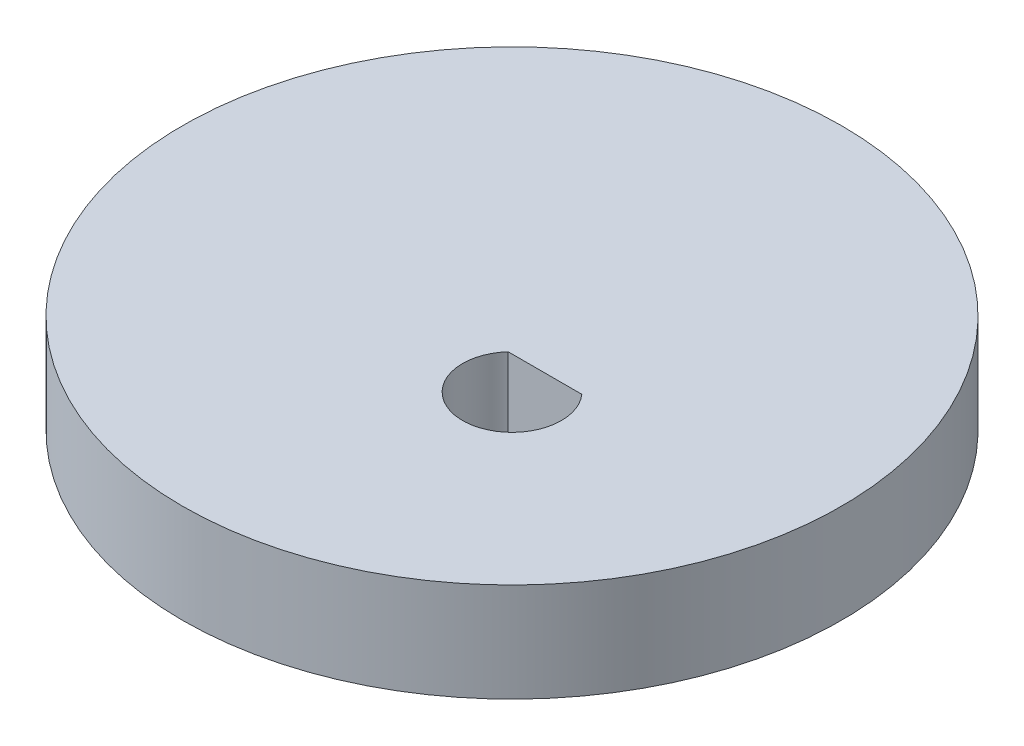
SolidWorks part; units mm, degrees
ref_plane "Front Plane" through (0, 0, 0) normal (0, 0, 1) x (1, 0, 0)
ref_plane "Top Plane" through (0, 0, 0) normal (0, 1, 0) x (1, 0, 0)
ref_plane "Right Plane" through (0, 0, 0) normal (1, 0, 0) x (0, 0, -1)
sketch "Sketch1" plane through (0, 0, 0) normal (0, 1, 0) x (1, 0, 0)
  circle A0 centre (0, 0) radius 10
  dimension "D1" = 20
extrude "Boss-Extrude1" add sketch "Sketch1" along normal blind 3 contours A0
sketch "Sketch6" plane through (0, 3, 0) normal (0, 1, 0) x (1, 0, 0)
  line L3 (0.882, -1) -> (3.118, -1)
  arc A0 (0.882, -1) -> (3.118, -1) centre (2, -2) ccw
  point P2 (2, -0.5)
  dimension "D1" = 3
  dimension "D4" = 2
  dimension "D5" = 2
extrude "Cut-Extrude2" cut sketch "Sketch6" against normal blind 3
